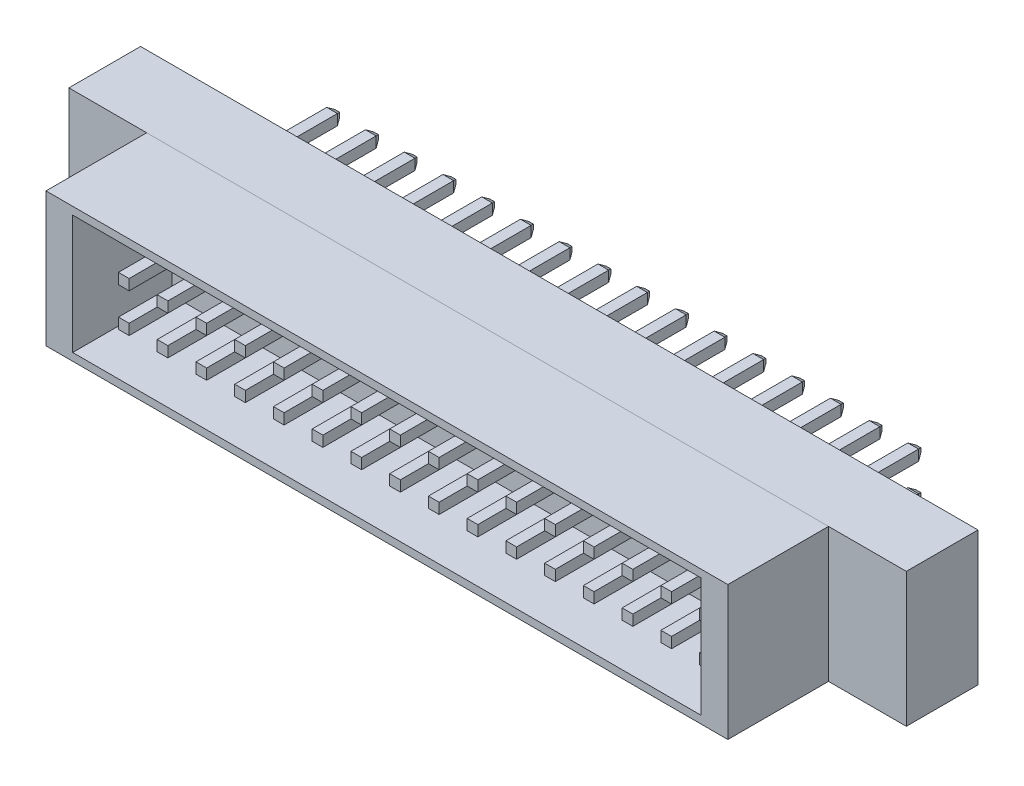
SolidWorks part; units mm, degrees
other "Детальный элемент1"
ref_plane "Спереди" through (0, 0, 0) normal (0, 0, 1) x (1, 0, 0)
ref_plane "Сверху" through (0, 0, 0) normal (0, 1, 0) x (1, 0, 0)
ref_plane "Справа" through (0, 0, 0) normal (1, 0, 0) x (0, 0, -1)
sketch "Эскиз1" plane through (0, 0, 0) normal (0, 0, 1) x (1, 0, 0)
  line L1 (-19.4, 2.89) -> (-18.7, 2.89)
  line L2 (-19.4, 2.89) -> (-19.4, 2.19)
  line L3 (-19.4, 2.19) -> (-18.7, 2.19)
  line L4 (-18.7, 2.89) -> (-18.7, 2.19)
  line L5 (-19.4, 2.89) -> (-18.7, 2.19) construction
  line L6 (-19.4, 2.19) -> (-18.7, 2.89) construction
  point P0 (-19.05, 2.54)
  dimension "D1" = 0.7
  dimension "D2" = 19.05
  dimension "D3" = 2.54
extrude "Бобышка-Вытянуть1" add sketch "Эскиз1" along normal blind 9.5 and the other way blind 4.5
chamfer "Фаска1" distance 0.2 angle 60 4 edges at (-19.4, 2.54, -4.5) (-19.05, 2.19, -4.5) (-18.7, 2.54, -4.5) (-19.05, 2.89, -4.5)
pattern_linear "Линейный массив1" count 3 spacing 2.54 along (0, -1, 0) count 16 spacing 2.54 along (1, 0, 0) of bodies 107
sketch "Эскиз2" plane through (0, 0, 0) normal (0, 0, 1) x (1, 0, 0)
  line L1 (27.45, 4.4) -> (-27.45, 4.4)
  line L2 (27.45, 4.4) -> (27.45, -4.4)
  line L3 (27.45, -4.4) -> (-27.45, -4.4)
  line L4 (-27.45, 4.4) -> (-27.45, -4.4)
  line L5 (27.45, 4.4) -> (-27.45, -4.4) construction
  line L6 (27.45, -4.4) -> (-27.45, 4.4) construction
  point P0 (0, 0)
  dimension "D1" = 54.9
  dimension "D2" = 8.8
extrude "Бобышка-Вытянуть2" add sketch "Эскиз2" along normal blind 4.7 separate body
sketch "Эскиз3" plane through (0, 0, 4.7) normal (0, 0, 1) x (1, 0, 0)
  line L0 (27.45, 4.4) -> (-27.45, 4.4) construction
  line L1 (-22.35, -4.4) -> (22.35, -4.4)
  line L2 (-22.35, -4.4) -> (-22.35, 4.4)
  line L3 (-22.35, 4.4) -> (22.35, 4.4)
  line L4 (22.35, -4.4) -> (22.35, 4.4)
  line L5 (-22.35, -4.4) -> (22.35, 4.4) construction
  line L6 (-22.35, 4.4) -> (22.35, -4.4) construction
  point P0 (0, 0)
  dimension "D1" = 44.7
extrude "Бобышка-Вытянуть3" add sketch "Эскиз3" along normal blind 6.6 separate body
shell "Оболочка1" thickness 0.1
